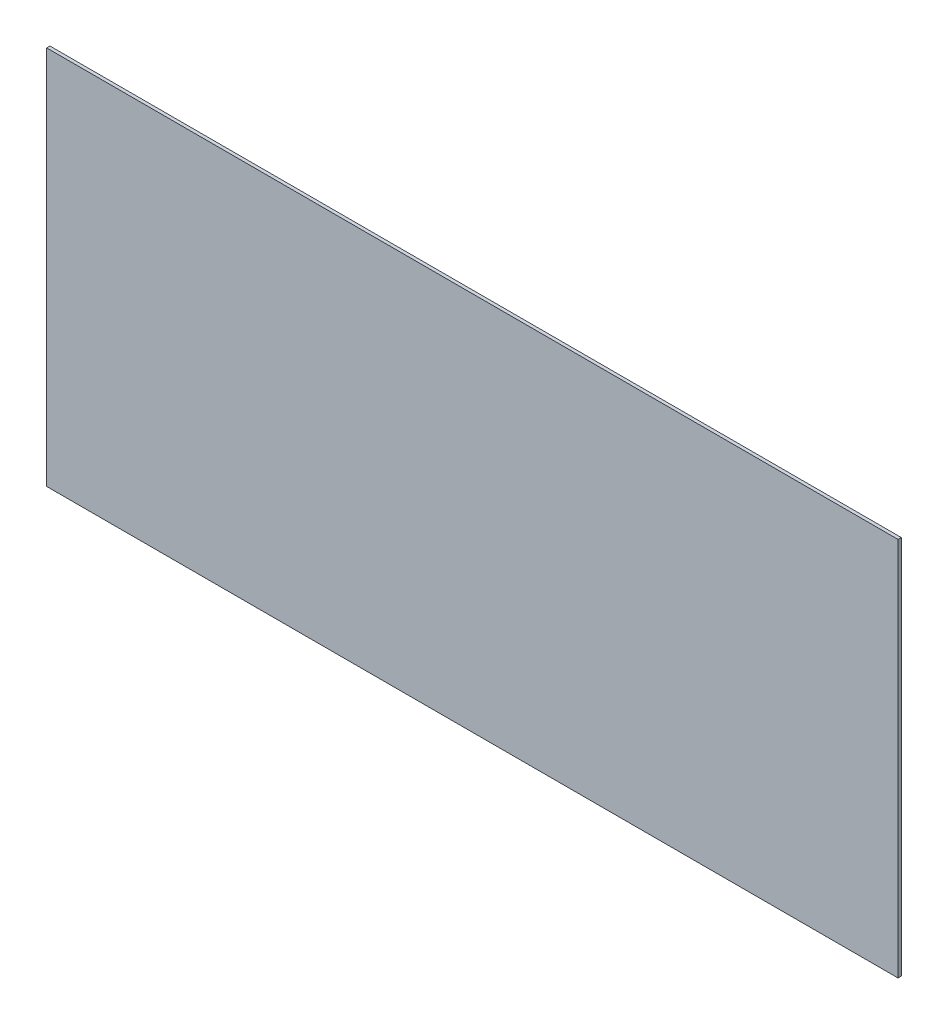
SolidWorks part; units mm, degrees
ref_plane "Plan de face" through (0, 0, 0) normal (0, 0, 1) x (1, 0, 0)
ref_plane "Plan de dessus" through (0, 0, 0) normal (0, 1, 0) x (1, 0, 0)
ref_plane "Plan de droite" through (0, 0, 0) normal (1, 0, 0) x (0, 0, -1)
sketch "Esquisse1" plane through (0, 0, 0) normal (0, 0, 1) x (1, 0, 0)
  line L1 (0, 0) -> (26, 0)
  line L2 (0, 0) -> (0, 11.6)
  line L3 (0, 11.6) -> (26, 11.6)
  line L4 (26, 0) -> (26, 11.6)
  dimension "D1" = 26
  dimension "D2" = 11.6
extrude "Boss.-Extru.1" add sketch "Esquisse1" along normal blind 0.1
